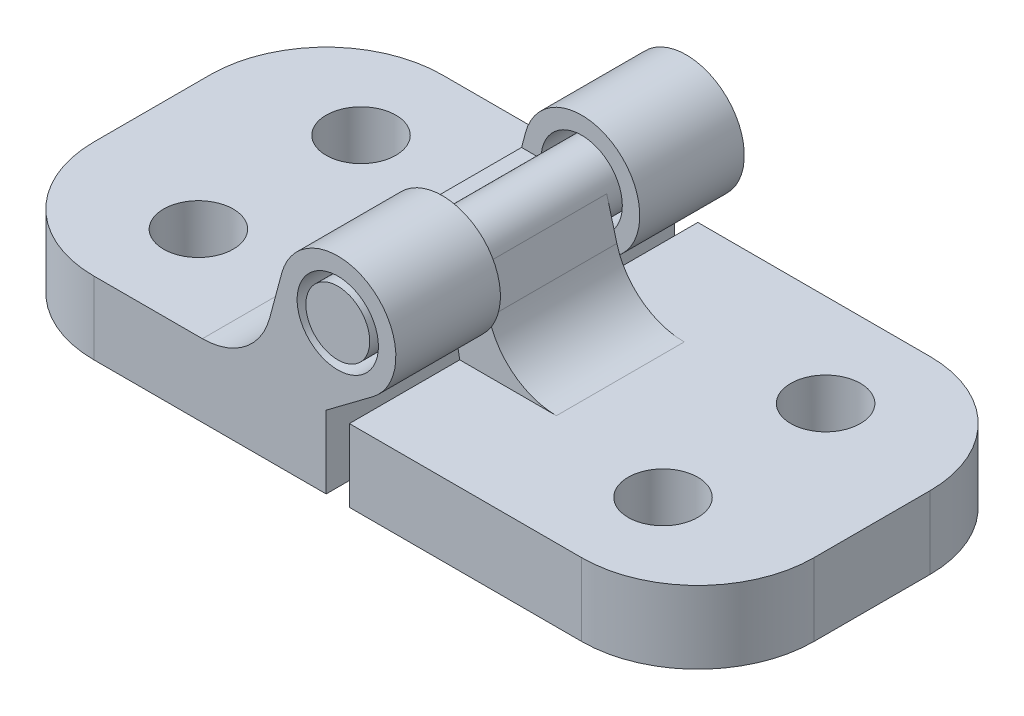
SolidWorks part; units mm, degrees
ref_plane "Front Plane" through (0, 0, 0) normal (0, 0, 1) x (1, 0, 0)
ref_plane "Top Plane" through (0, 0, 0) normal (0, 1, 0) x (1, 0, 0)
ref_plane "Right Plane" through (0, 0, 0) normal (1, 0, 0) x (0, 0, -1)
sketch "Sketch2" plane through (0, 0, 0) normal (0, 1, 0) x (1, 0, 0)
  line L0 (0, -55) -> (0, 55) construction
  line L5 (-55, 0) -> (55, 0) construction
  line L6 (-15.5, -7.5) -> (-0.5, -7.5)
  line L7 (-15.5, -7.5) -> (-15.5, 7.5)
  line L12 (-15.5, 7.5) -> (-0.5, 7.5)
  line L13 (-0.5, -7.5) -> (-0.5, 7.5)
  line L14 (-15.5, -7.5) -> (-0.5, 7.5) construction
  line L15 (-15.5, 7.5) -> (-0.5, -7.5) construction
  line L17 (15.5, 7.5) -> (0.5, -7.5) construction
  line L18 (15.5, -7.5) -> (0.5, 7.5) construction
  line L19 (0.5, -7.5) -> (0.5, 7.5)
  line L20 (15.5, 7.5) -> (0.5, 7.5)
  line L21 (15.5, -7.5) -> (15.5, 7.5)
  line L22 (15.5, -7.5) -> (0.5, -7.5)
  point P0 (-8, 0)
  point P14 (8, 0)
  dimension "D1" = 15
  dimension "D2" = 15
  dimension "D3" = 8
extrude "Boss-Extrude1" add sketch "Sketch2" along normal blind 3.125 contours L7 L12 L13 L6 | L22 L19 L20 L21
sketch "Sketch3" plane through (0, 0, 7.5) normal (0, 0, 1) x (1, 0, 0)
  line L0 (-15.5, 3.125) -> (-0.5, 3.125) construction
  line L1 (-0.5, 3.125) -> (1.5, 4.625)
  line L2 (-2.4148, 7.272) -> (-3.526, 3.125)
  line L3 (-3.526, 3.125) -> (-0.5, 3.125)
  line L4 (-0.5, 3.125) -> (-0.5, 0) construction
  arc A0 (1.5, 4.625) -> (-2.4148, 7.272) centre (0, 6.625) ccw
  circle A1 centre (0, 6.625) radius 1.75
  dimension "D1" = 5
  dimension "D3" = 3.5
  dimension "D2" = 3.5
  dimension "D4" = 0.5
  dimension "D5" = 75
extrude "Boss-Extrude2" add sketch "Sketch3" against normal up to surface (15 mm away) up to face at (-8, 1.5625, -7.5)
sketch "Sketch4" plane through (0, 0, 0) normal (1, 0, 0) x (0, 0, -1)
  line L1 (-3, 3.375) -> (3, 3.375)
  line L2 (-3, 3.375) -> (-3, 9.125)
  line L3 (-3, 9.125) -> (3, 9.125)
  line L4 (3, 3.375) -> (3, 9.125)
  line L5 (-3, 3.375) -> (3, 9.125) construction
  line L6 (-3, 9.125) -> (3, 3.375) construction
  line L8 (7.5, 9.125) -> (-7.5, 9.125) construction
  line L9 (0, 5.0187) -> (0, -5.0187) construction
  line L11 (-7.5, 3.125) -> (7.5, 3.125) construction
  point P0 (0, 6.25)
  dimension "D2" = 6
  dimension "D3" = 3
  dimension "D1" = 0.25
extrude "Cut-Extrude1" cut sketch "Sketch4" along normal up to next
sketch "Sketch9" plane through (0, 0, 0) normal (1, 0, 0) x (0, 0, -1)
  line L1 (-3, 9.125) -> (3, 9.125)
  line L2 (-3, 9.125) -> (-3, 6.625)
  line L3 (-3, 6.625) -> (3, 6.625)
  line L4 (3, 9.125) -> (3, 6.625)
  line L5 (3, 9.125) -> (-3, 9.125) construction
  line L6 (-3, 9.125) -> (-3, 8.375) construction
  line L8 (3, 8.375) -> (3, 9.125) construction
  dimension "D1" = 2.5
extrude "Cut-Extrude4" cut sketch "Sketch9" against normal up to next
sketch "Sketch5" plane through (0, 0, 0) normal (0, 0, 1) x (1, 0, 0)
  line L0 (0.1243, 5.2556) -> (0.5, 3.125)
  line L1 (0.5, 3.125) -> (2.3613, 3.125)
  line L2 (2.3613, 3.125) -> (1.3281, 6.9809)
  line L3 (15.5, 3.125) -> (0.5, 3.125) construction
  arc A0 (1.3281, 6.9809) -> (0.1243, 5.2556) centre (0, 6.625) ccw
  circle A1 centre (0, 6.625) radius 1.75 construction
  dimension "D1" = 2.75
  dimension "D2" = 100
  dimension "D3" = 75
extrude "Boss-Extrude3" add sketch "Sketch5" along normal offset from surface 0.25 and the other way offset from surface (2.75 mm away) 0.25 up to face at (-0.2138, 6.397, 3) other way up to face at (-0.2138, 6.397, -3)
sketch "Sketch7" plane through (0, 0, 0) normal (0, 0, 1) x (1, 0, 0)
  circle A0 centre (0, 6.625) radius 1.375
  arc A2 (1.3281, 6.9809) -> (0.1243, 5.2556) centre (0, 6.625) ccw construction
extrude "Boss-Extrude4" add sketch "Sketch7" along normal up to surface and the other way up to surface
sketch "Sketch8" plane through (0, 3.125, 0) normal (0, 1, 0) x (1, 0, 0)
  line L0 (-5.0187, 0) -> (5.0187, 0) construction
  line L1 (0, -5.0187) -> (0, 5.0187) construction
  circle A0 centre (-10, 3.5) radius 1.5
  circle A1 centre (-10, -3.5) radius 1.5
  circle A2 centre (10, -3.5) radius 1.5
  circle A3 centre (10, 3.5) radius 1.5
  dimension "D1" = 3
  dimension "D2" = 3.5
  dimension "D3" = 10
extrude "Cut-Extrude2" cut sketch "Sketch8" against normal up to next (3.125 mm away)
fillet "Fillet1" radius 5 2 edges at (-15.5, 1.5625, -7.5) (-15.5, 1.5625, 7.5)
fillet "Fillet2" radius 5 2 edges at (15.5, 1.5625, 7.5) (15.5, 1.5625, -7.5)
fillet "Fillet3" radius 3 1 edges at (-3.526, 3.125, 0)
fillet "Fillet4" radius 3 1 edges at (2.3613, 3.125, 0)
equation "\"D3@Sketch2\"=\"D2@Sketch2\"/2+.5"
equation "\"D2@Sketch3\"=\"D1@Sketch3\"/2+1"
equation "\"D3@Sketch4\"=\"D2@Sketch4\"/2"
